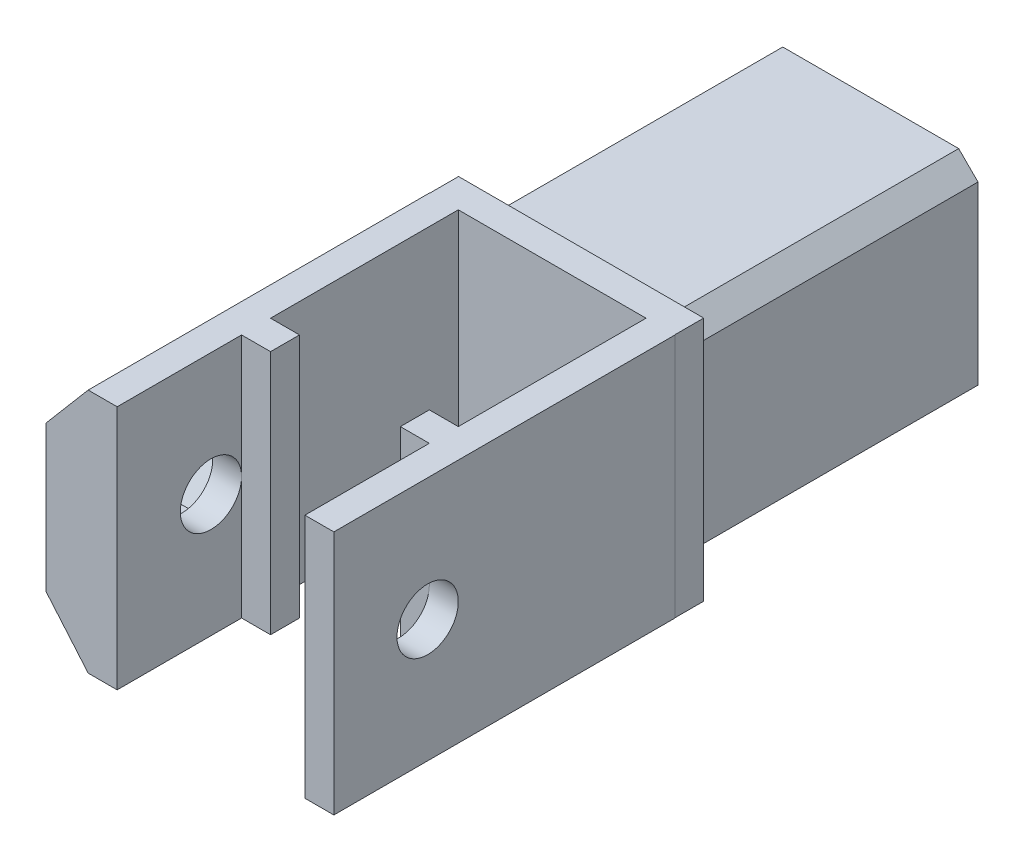
SolidWorks part; units mm, degrees
ref_plane "Front Plane" through (0, 0, 0) normal (0, 0, 1) x (1, 0, 0)
ref_plane "Top Plane" through (0, 0, 0) normal (0, 1, 0) x (1, 0, 0)
ref_plane "Right Plane" through (0, 0, 0) normal (1, 0, 0) x (0, 0, -1)
sketch "Sketch1" plane through (0, 0, 0) normal (0, 0, 1) x (1, 0, 0)
  line L1 (-11.1125, -11.1125) -> (11.1125, -11.1125)
  line L2 (-11.1125, -11.1125) -> (-11.1125, 11.1125)
  line L3 (-11.1125, 11.1125) -> (11.1125, 11.1125)
  line L4 (11.1125, -11.1125) -> (11.1125, 11.1125)
  line L5 (-11.1125, -11.1125) -> (11.1125, 11.1125) construction
  line L6 (-11.1125, 11.1125) -> (11.1125, -11.1125) construction
  point P0 (0, 0)
  dimension "D1" = 22.225
extrude "Boss-Extrude1" add sketch "Sketch1" along normal blind 30
sketch "Sketch3" plane through (0, 0, 30) normal (0, 0, 1) x (1, 0, 0)
  line L1 (-12.7, -12.7) -> (12.7, -12.7)
  line L2 (-12.7, -12.7) -> (-12.7, 12.7)
  line L3 (-12.7, 12.7) -> (12.7, 12.7)
  line L4 (12.7, -12.7) -> (12.7, 12.7)
  line L5 (-12.7, -12.7) -> (12.7, 12.7) construction
  line L6 (-12.7, 12.7) -> (12.7, -12.7) construction
  point P0 (0, 0)
  dimension "D1" = 25.4
extrude "Boss-Extrude2" add sketch "Sketch3" along normal blind 3
sketch "Sketch4" plane through (0, 12.7, 0) normal (0, 1, 0) x (1, 0, 0)
  line L0 (-12.725, -33) -> (-12.725, -68.34)
  line L1 (12.7, -33) -> (-12.7, -33) construction
  line L2 (-12.725, -68.34) -> (-9.725, -68.34)
  line L3 (-9.725, -68.34) -> (-9.725, -55.45)
  line L4 (-9.725, -55.45) -> (-6.725, -55.45)
  line L5 (-6.725, -55.45) -> (-6.725, -52.45)
  line L6 (-6.725, -52.45) -> (-9.725, -52.45)
  line L7 (-9.725, -52.45) -> (-9.725, -33)
  line L8 (-9.725, -33) -> (-12.725, -33)
  line L9 (0, -33) -> (0, -68.34) construction
  line L10 (9.725, -33) -> (12.725, -33)
  line L11 (9.725, -52.45) -> (9.725, -33)
  line L12 (6.725, -52.45) -> (9.725, -52.45)
  line L13 (6.725, -55.45) -> (6.725, -52.45)
  line L14 (9.725, -55.45) -> (6.725, -55.45)
  line L15 (9.725, -68.34) -> (9.725, -55.45)
  line L16 (12.725, -68.34) -> (9.725, -68.34)
  line L17 (12.725, -33) -> (12.725, -68.34)
  line L18 (-9.725, -33) -> (9.725, -33) construction
  dimension "D1" = 19.45
  dimension "D2" = 3
  dimension "D3" = 3
  dimension "D4" = 12.89
extrude "Boss-Extrude3" add sketch "Sketch4" against normal up to surface (25.4 mm away) up to face at (0, -12.7, 31.5)
sketch "Sketch6" plane through (0, 0, 68.34) normal (0, 0, 1) x (1, 0, 0)
  line L0 (-12.725, -12.7) -> (-17.095, -7.555)
  line L1 (-9.725, -12.7) -> (-12.725, -12.7) construction
  line L2 (-17.095, -7.555) -> (-17.095, 7.555)
  line L3 (-17.095, 7.555) -> (-12.725, 12.7)
  line L4 (-12.725, 12.7) -> (-12.725, -12.7)
  line L7 (-17.095, 0) -> (-12.725, 0) construction
  line L9 (-12.725, 12.7) -> (-9.725, 12.7) construction
  point P2 (-12.525, -12.7)
  point P3 (-12.5272, -12.7)
  point P9 (-12.5248, 12.7)
  point P11 (-19.6706, 0)
  point P13 (0, 0)
  dimension "D1" = 15.11
  dimension "D2" = 4.37
extrude "Boss-Extrude4" add sketch "Sketch6" against normal blind 19.43
sketch "Sketch5" plane through (9.725, 0, 0) normal (-1, 0, 0) x (0, 0, 1)
  line L0 (55.45, -12.7) -> (55.45, 12.7) construction
  circle A0 centre (58.625, 0) radius 3.175
  dimension "D1" = 6.35
extrude "Cut-Extrude1" cut sketch "Sketch5" against normal through all both and the other way through all
sketch "Sketch7" plane through (-17.095, 0, 0) normal (-1, 0, 0) x (0, 0, 1)
  line L1 (61.9765, 5.805) -> (55.2735, 5.805)
  line L2 (55.2735, 5.805) -> (51.922, 0)
  line L3 (51.922, 0) -> (55.2735, -5.805)
  line L4 (55.2735, -5.805) -> (61.9765, -5.805)
  line L5 (61.9765, -5.805) -> (65.328, 0)
  line L6 (65.328, 0) -> (61.9765, 5.805)
  circle A0 centre (58.625, 0) radius 5.805 construction
  dimension "D1" = 11.61
extrude "Cut-Extrude2" cut sketch "Sketch7" against normal blind 4.38
chamfer "Chamfer1" distance 2 angle 45 4 edges at (-11.1125, -11.1125, 15) (-11.1125, 11.1125, 15) (11.1125, -11.1125, 15) (11.1125, 11.1125, 15)
equation "\"D4@Sketch4\"=.25in/2+12.83/2+3+.3"
